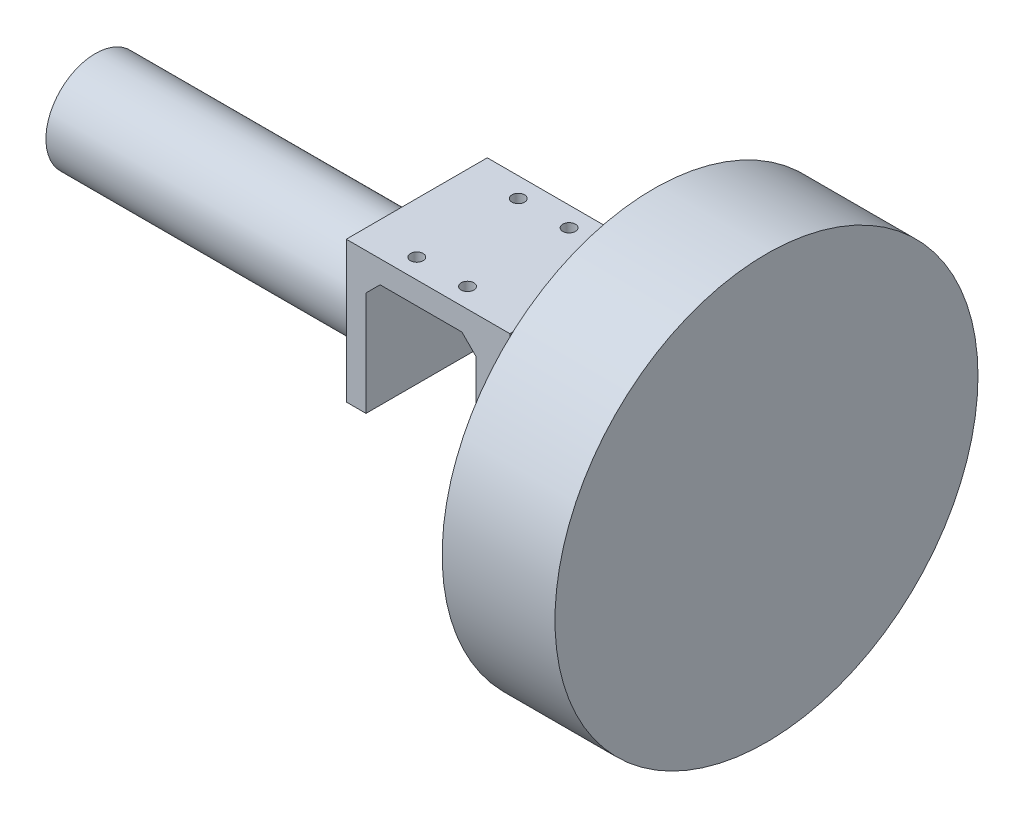
SolidWorks part; units mm, degrees
ref_plane "Płaszczyzna przednia" through (0, 0, 0) normal (0, 0, 1) x (1, 0, 0)
ref_plane "Płaszczyzna górna" through (0, 0, 0) normal (0, 1, 0) x (1, 0, 0)
ref_plane "Płaszczyzna prawa" through (0, 0, 0) normal (1, 0, 0) x (0, 0, -1)
sketch "Szkic1" plane through (0, 0, 0) normal (1, 0, 0) x (0, 0, -1)
  circle A0 centre (0, 0) radius 75
  dimension "D1" = 150
extrude "Dodanie-wyciągnięcie1" add sketch "Szkic1" along normal mid plane 40
sketch "Szkic2" plane through (-20, 0, 0) normal (-1, 0, 0) x (0, 0, 1)
  circle A0 centre (0, 0) radius 14
  dimension "D1" = 28
extrude "Dodanie-wyciągnięcie2" add sketch "Szkic2" along normal blind 20
sketch "Szkic3" plane through (-40, 0, 0) normal (-1, 0, 0) x (0, 0, 1)
  circle A0 centre (0, 0) radius 7
  dimension "D1" = 14
extrude "Dodanie-wyciągnięcie3" add sketch "Szkic3" along normal blind 6
sketch "Szkic4" plane through (0, 0, 0) normal (0, 0, 1) x (1, 0, 0)
  line L0 (-46, -20) -> (-46, 30)
  line L1 (-46, 30) -> (-104, 30)
  line L2 (-104, 30) -> (-104, -20)
  line L3 (-104, -20) -> (-97, -20)
  line L4 (-97, -20) -> (-97, 22)
  line L5 (-97, 22) -> (-58, 22)
  line L6 (-58, 22) -> (-58, -20)
  line L7 (-58, -20) -> (-46, -20)
  line L8 (-46, 7) -> (-46, -7) construction
  line L9 (-40, 0) -> (49960, 0) construction
  line L10 (-40, 7) -> (-40, -7) construction
  point P14 (-40, 0)
  dimension "D1" = 12
  dimension "D2" = 58
  dimension "D3" = 50
  dimension "D4" = 8
  dimension "D5" = 30
  dimension "D6" = 7
extrude "Dodanie-wyciągnięcie4" add sketch "Szkic4" along normal mid plane 50
chamfer "Sfazowanie1" distance 5 angle 45 2 edges at (-58, 22, 0) (-97, 22, 0)
sketch "Szkic5" plane through (-104, 0, 0) normal (-1, 0, 0) x (0, 0, 1)
  circle A0 centre (0, 0) radius 17.5
  dimension "D1" = 35
extrude "Dodanie-wyciągnięcie5" add sketch "Szkic5" along normal blind 114
hole_wizard "Otwór pod śrubę M41" positions "Szkic6" profile "Szkic7" hole size "M4" standard "ISO" end condition through all
sketch "Szkic6" plane through (0, 30, 0) normal (0, 1, 0) x (1, 0, 0)
  line L0 (0, 0) -> (50000, 0) construction
  line L1 (-46, -25) -> (-46, 25) construction
  point P0 (-68, 18)
  point P2 (-86, 18)
  point P9 (0, 0)
  point P10 (-68, -18)
  point P11 (-86, -18)
  point P14 (0, 0)
  dimension "D1" = 36
  dimension "D2" = 22
  dimension "D3" = 18
sketch "Szkic7" plane through (-68, 30, -18) normal (1, 0, 0) x (0, 0, 1)
  line L0 (0, 0) -> (0, 105)
  line L1 (0, 105) -> (2.25, 105)
  line L2 (2.25, 105) -> (2.25, 0)
  line L5 (2.25, 0) -> (0, 0)
  line L11 (0, -6.35) -> (0, 107.95) construction
  dimension "Średnica otworu na wylot" = 4.5
  dimension "Głębokość otworu na wylot" = 105
